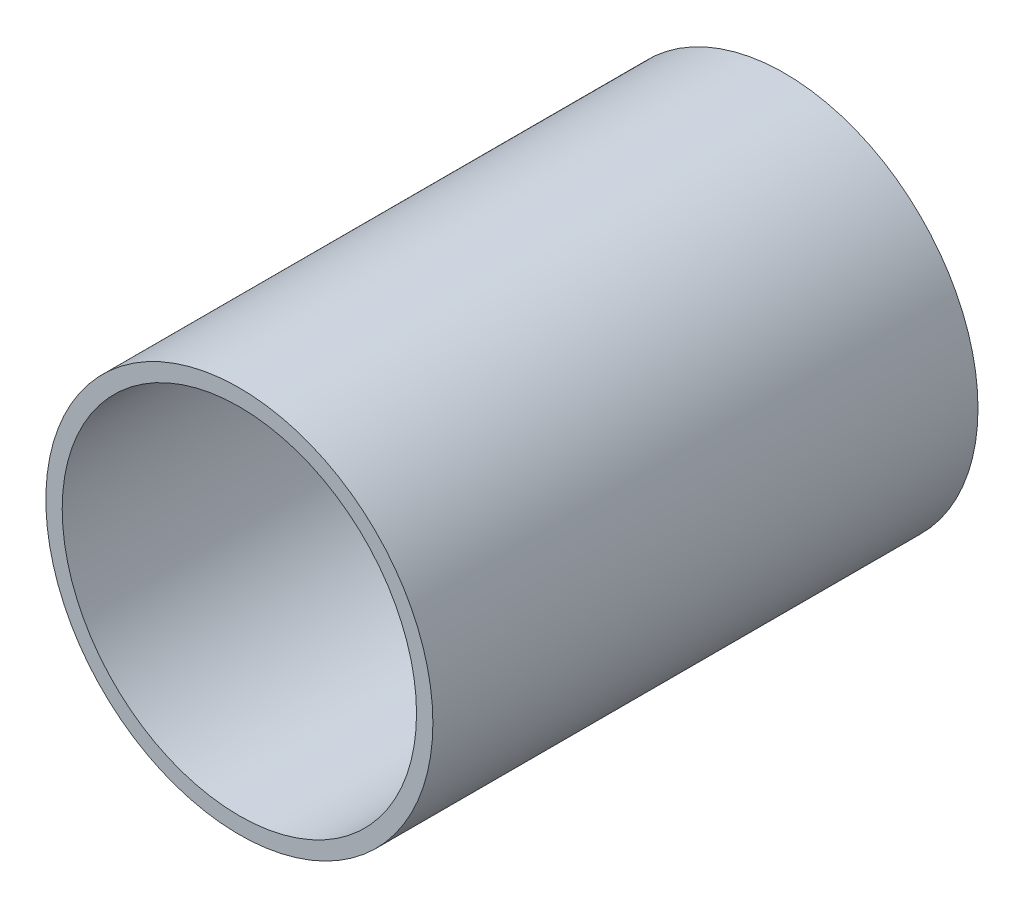
SolidWorks part; units mm, degrees
ref_plane "Plan de face" through (0, 0, 0) normal (0, 0, 1) x (1, 0, 0)
ref_plane "Plan de dessus" through (0, 0, 0) normal (0, 1, 0) x (1, 0, 0)
ref_plane "Plan de droite" through (0, 0, 0) normal (1, 0, 0) x (0, 0, -1)
sketch "Esquisse1" plane through (0, 0, 0) normal (0, 0, 1) x (1, 0, 0)
  circle A0 centre (0, 0) radius 32.5
  circle A1 centre (0, 0) radius 35.5
  dimension "D1" = 65
  dimension "D2" = 71
extrude "Boss.-Extru.1" add sketch "Esquisse1" along normal blind 100
